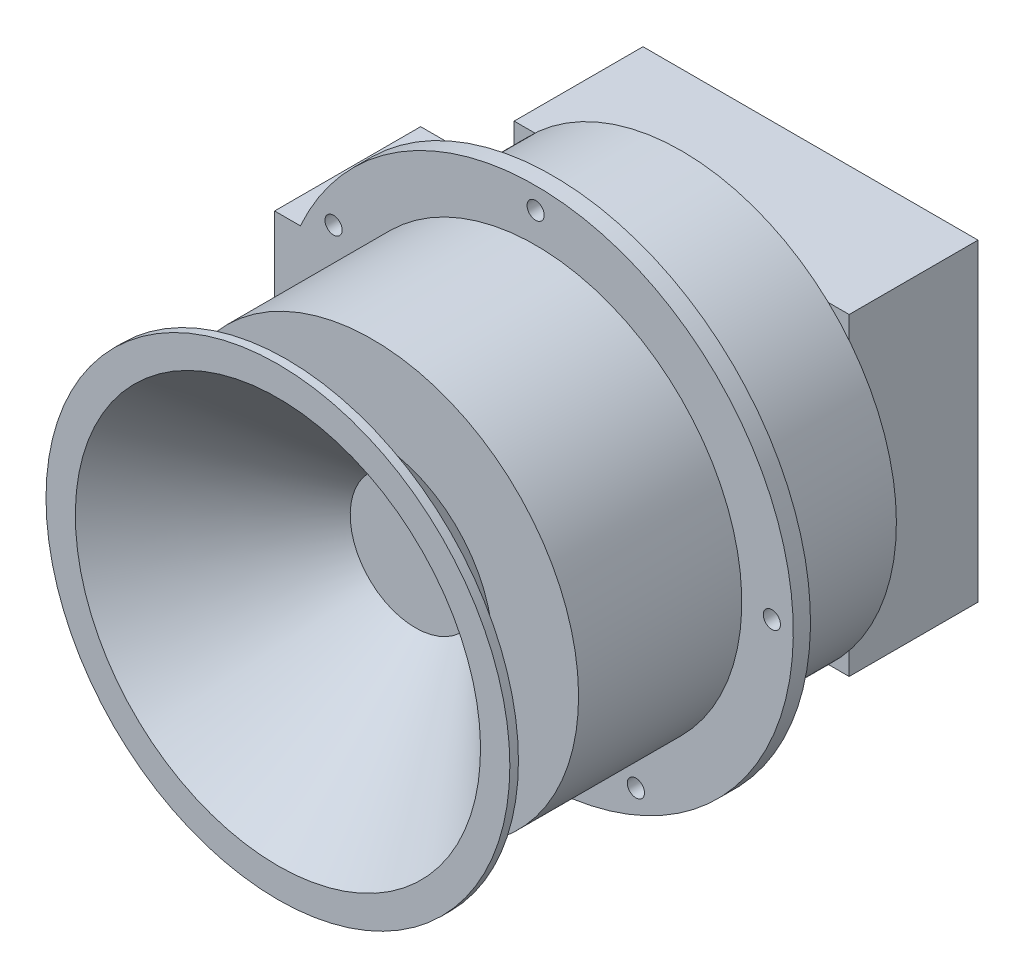
SolidWorks part; units mm, degrees
ref_plane "Front Plane" through (0, 0, 0) normal (0, 0, 1) x (1, 0, 0)
ref_plane "Top Plane" through (0, 0, 0) normal (0, 1, 0) x (1, 0, 0)
ref_plane "Right Plane" through (0, 0, 0) normal (1, 0, 0) x (0, 0, -1)
sketch "Sketch1" plane through (0, 0, 0) normal (0, 0, 1) x (1, 0, 0)
  line L0 (-27.387, 12.2455) -> (-30.387, 12.2455)
  line L1 (-30.387, 12.2455) -> (-30.387, -4.7545)
  line L2 (-30.387, -4.7545) -> (-25.2914, -18.7545)
  line L3 (-25.2914, -18.7545) -> (-23.4151, -18.7545)
  arc A0 (-23.4151, -18.7545) -> (-27.387, 12.2455) centre (0, 0) ccw
  circle A1 centre (0, 0) radius 27.5 construction
  circle A2 centre (0, 27.5) radius 1
  circle A3 centre (-23.5227, 14.2455) radius 1
  circle A4 centre (27.5, 0) radius 1
  circle A5 centre (11.6773, -24.8976) radius 1
  point P19 (-35.4055, 4.9451)
  dimension "D1" = 60
  dimension "D2" = 55
  dimension "D3" = 2
  dimension "D4" = 27
  dimension "D5" = 29.5
  dimension "D6" = 3
  dimension "D7" = 31
  dimension "D8" = 2
  dimension "D9" = 200
  dimension "D10" = 17
extrude "Boss-Extrude1" add sketch "Sketch1" along normal blind 2
sketch "Sketch2" plane through (0, 0, 0) normal (0, 0, -1) x (-1, 0, 0)
  line L0 (25.2914, -18.7545) -> (23.4151, -18.7545) construction
  line L1 (30.387, -4.7545) -> (25.2914, -18.7545) construction
  line L2 (30.387, 12.2455) -> (30.387, -4.7545) construction
  line L3 (27.387, 12.2455) -> (30.387, 12.2455) construction
  line L4 (25.2914, -18.7545) -> (23.4151, -18.7545)
  line L5 (30.387, -4.7545) -> (25.2914, -18.7545)
  line L6 (30.387, 12.2455) -> (30.387, -4.7545)
  line L7 (27.387, 12.2455) -> (30.387, 12.2455)
  line L8 (27.387, 12.2455) -> (21.7956, 12.2455)
  line L9 (23.4151, -18.7545) -> (16.5308, -18.7545)
  arc A0 (21.7956, 12.2455) -> (16.5308, -18.7545) centre (0, 0) ccw
  point P7 (21.7956, 12.2455)
  dimension "D1" = 50
extrude "Boss-Extrude2" add sketch "Sketch2" along normal blind 15
sketch "Sketch3" plane through (0, 0, -15) normal (0, 0, -1) x (-1, 0, 0)
  line L1 (-19.5, -18.25) -> (19.5, -18.25)
  line L2 (-19.5, -18.25) -> (-19.5, 18.25)
  line L3 (-19.5, 18.25) -> (19.5, 18.25)
  line L4 (19.5, -18.25) -> (19.5, 18.25)
  line L5 (-19.5, -18.25) -> (19.5, 18.25) construction
  line L6 (-19.5, 18.25) -> (19.5, -18.25) construction
  point P0 (0, 0)
  dimension "D1" = 39
  dimension "D2" = 36.5
extrude "Boss-Extrude3" add sketch "Sketch3" along normal blind 15 separate body
sketch "Sketch4" plane through (0, 0, 2) normal (0, 0, 1) x (1, 0, 0)
  circle A0 centre (0, 0) radius 24
  dimension "D1" = 48
extrude "Boss-Extrude4" add sketch "Sketch4" along normal blind 13
sketch "Sketch5" plane through (0, 0, 0) normal (1, 0, 0) x (0, 0, -1)
  line L0 (-15, 0) -> (-15, 24)
  line L1 (-15, 24) -> (-15, -24) construction
  line L2 (-15, 24) -> (-21, 24)
  line L3 (-21, 24) -> (-21, 14)
  line L4 (-21, 14) -> (-31, 24)
  line L5 (-31, 24) -> (-31, 27)
  line L6 (-31, 27) -> (-32, 27)
  line L7 (-32, 27) -> (-32, 23.5858)
  line L8 (-32, 23.5858) -> (-16, 7.5858)
  line L9 (-16, 7.5858) -> (-16, 0)
  line L10 (-16, 0) -> (-15, 0)
  point P8 (0, 0)
  dimension "D1" = 6
  dimension "D2" = 1
  dimension "D3" = 1
  dimension "D4" = 3
  dimension "D5" = 10
  dimension "D6" = 45
  dimension "D7" = 1
revolve "Revolve1" add sketch "Sketch5" angle 360 about L10
sketch "Sketch6" plane through (0, 0, 2) normal (0, 0, 1) x (1, 0, 0)
  circle A0 centre (-24, 0) radius 5
  circle A1 centre (0, 0) radius 24 construction
  point P4 (0, 0)
  dimension "D1" = 10
extrude "Boss-Extrude5" add sketch "Sketch6" along normal blind 6.5
